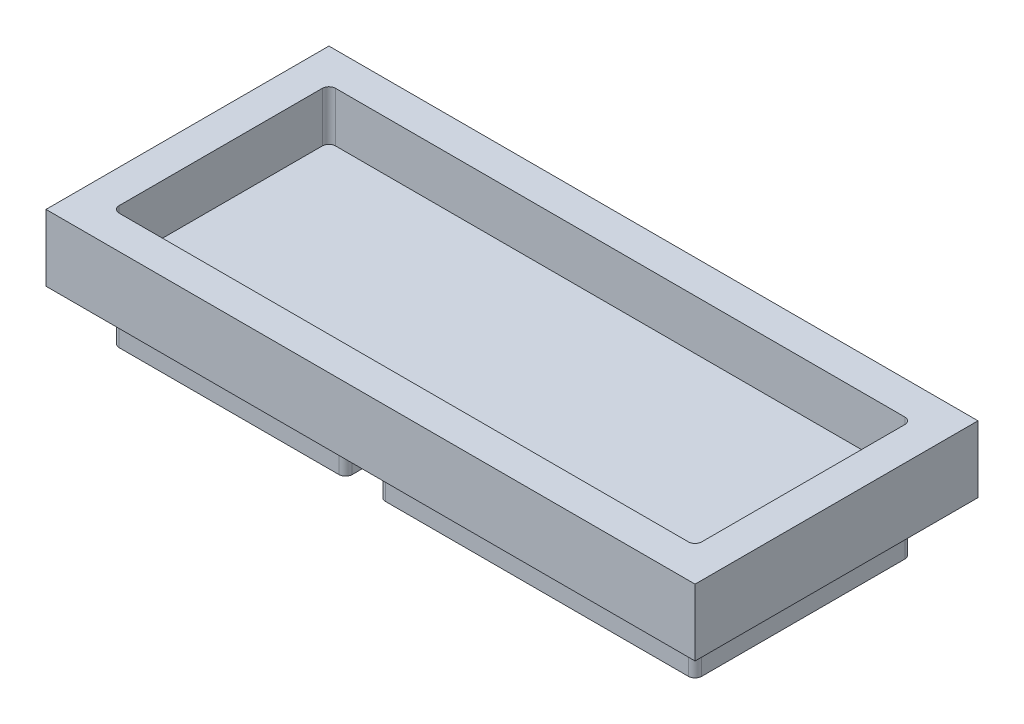
SolidWorks part; units mm, degrees
ref_plane "Front Plane" through (0, 0, 0) normal (0, 0, 1) x (1, 0, 0)
ref_plane "Top Plane" through (0, 0, 0) normal (0, 1, 0) x (1, 0, 0)
ref_plane "Right Plane" through (0, 0, 0) normal (1, 0, 0) x (0, 0, -1)
sketch "Sketch1" plane through (0, 0, 0) normal (0, 1, 0) x (1, 0, 0)
  line L0 (-74.8482, -3.7054) -> (-74.8482, 57.2946)
  line L1 (-84.8482, -15.7054) -> (110.1518, -15.7054)
  line L2 (-84.8482, -15.7054) -> (-84.8482, 69.2946)
  line L3 (-84.8482, 69.2946) -> (110.1518, 69.2946)
  line L4 (110.1518, -15.7054) -> (110.1518, 69.2946)
  line L5 (-72.8482, 59.2946) -> (-6.8482, 59.2946)
  line L6 (100.1518, -3.7054) -> (100.1518, 57.2946)
  line L7 (-72.8482, -5.7054) -> (-6.8482, -5.7054)
  line L8 (-4.8482, -3.7054) -> (-4.8482, 57.2946)
  line L9 (5.1518, -3.7054) -> (5.1518, 57.2946)
  line L10 (7.1518, -5.7054) -> (98.1518, -5.7054)
  line L11 (7.1518, 59.2946) -> (98.1518, 59.2946)
  line L12 (5.1518, -5.7054) -> (5.1518, 59.2946) construction
  line L13 (-4.8482, -5.7054) -> (-4.8482, 59.2946) construction
  line L14 (-74.8482, -5.7054) -> (-74.8482, 59.2946) construction
  arc A0 (5.1518, 57.2946) -> (7.1518, 59.2946) centre (7.1518, 57.2946) cw
  arc A1 (5.1518, -3.7054) -> (7.1518, -5.7054) centre (7.1518, -3.7054) ccw
  arc A2 (100.1518, -3.7054) -> (98.1518, -5.7054) centre (98.1518, -3.7054) cw
  arc A3 (98.1518, 59.2946) -> (100.1518, 57.2946) centre (98.1518, 57.2946) cw
  arc A4 (-4.8482, 57.2946) -> (-6.8482, 59.2946) centre (-6.8482, 57.2946) ccw
  arc A5 (-4.8482, -3.7054) -> (-6.8482, -5.7054) centre (-6.8482, -3.7054) cw
  arc A6 (-74.8482, 57.2946) -> (-72.8482, 59.2946) centre (-72.8482, 57.2946) cw
  arc A7 (-74.8482, -3.7054) -> (-72.8482, -5.7054) centre (-72.8482, -3.7054) ccw
  dimension "D5" = 2
  dimension "D1" = 195
  dimension "D2" = 85
  dimension "D3" = 70
  dimension "D4" = 10
extrude "Boss-Extrude2" add sketch "Sketch1" along normal blind 15 contours A4 L5 A6 L0 A7 L7 A5 L8 | L6 A3 L11 A0 L9 A1 L10 A2
sketch "Sketch2" plane through (0, 15, 0) normal (0, 1, 0) x (1, 0, 0)
  line L0 (-72.8482, 59.2946) -> (-6.8482, 59.2946) construction
  line L1 (-84.8482, 69.2946) -> (110.1518, 69.2946)
  line L2 (-84.8482, 69.2946) -> (-84.8482, -15.7054)
  line L3 (-84.8482, -15.7054) -> (110.1518, -15.7054)
  line L4 (110.1518, 69.2946) -> (110.1518, -15.7054)
  line L5 (-74.8482, -3.7054) -> (-74.8482, 57.2946) construction
  dimension "D1" = 195
  dimension "D2" = 85
  dimension "D3" = 10
  dimension "D4" = 10
extrude "Boss-Extrude3" add sketch "Sketch2" along normal blind 5
sketch "Sketch3" plane through (0, 20, 0) normal (0, 1, 0) x (1, 0, 0)
  line L0 (-74.8482, 57.2946) -> (-74.8482, -3.7054)
  line L1 (-72.8482, -5.7054) -> (98.1518, -5.7054)
  line L2 (100.1518, -3.7054) -> (100.1518, 57.2946)
  line L3 (98.1518, 59.2946) -> (-72.8482, 59.2946)
  line L4 (-84.8482, 69.2946) -> (-84.8482, -15.7054)
  line L5 (-84.8482, -15.7054) -> (110.1518, -15.7054)
  line L6 (110.1518, -15.7054) -> (110.1518, 69.2946)
  line L7 (110.1518, 69.2946) -> (-84.8482, 69.2946)
  line L8 (-84.8482, 69.2946) -> (-84.8482, -15.7054)
  line L9 (-84.8482, -15.7054) -> (110.1518, -15.7054)
  line L10 (110.1518, -15.7054) -> (110.1518, 69.2946)
  line L11 (110.1518, 69.2946) -> (-84.8482, 69.2946)
  line L12 (100.1518, -5.7054) -> (100.1518, 59.2946) construction
  line L13 (100.1518, 59.2946) -> (-74.8482, 59.2946) construction
  line L14 (-74.8482, -5.7054) -> (100.1518, -5.7054) construction
  line L15 (-74.8482, 59.2946) -> (-74.8482, -5.7054) construction
  arc A0 (100.1518, 57.2946) -> (98.1518, 59.2946) centre (98.1518, 57.2946) ccw
  arc A1 (98.1518, -5.7054) -> (100.1518, -3.7054) centre (98.1518, -3.7054) ccw
  arc A2 (-74.8482, -3.7054) -> (-72.8482, -5.7054) centre (-72.8482, -3.7054) ccw
  arc A3 (-74.8482, 57.2946) -> (-72.8482, 59.2946) centre (-72.8482, 57.2946) cw
  dimension "D3" = 2
  dimension "D1" = 0
  dimension "D2" = 10
extrude "Boss-Extrude4" add sketch "Sketch3" along normal blind 15 contours L8 L9 L10 L11 | A3 L3 A0 L2 A1 L1 A2 L0
